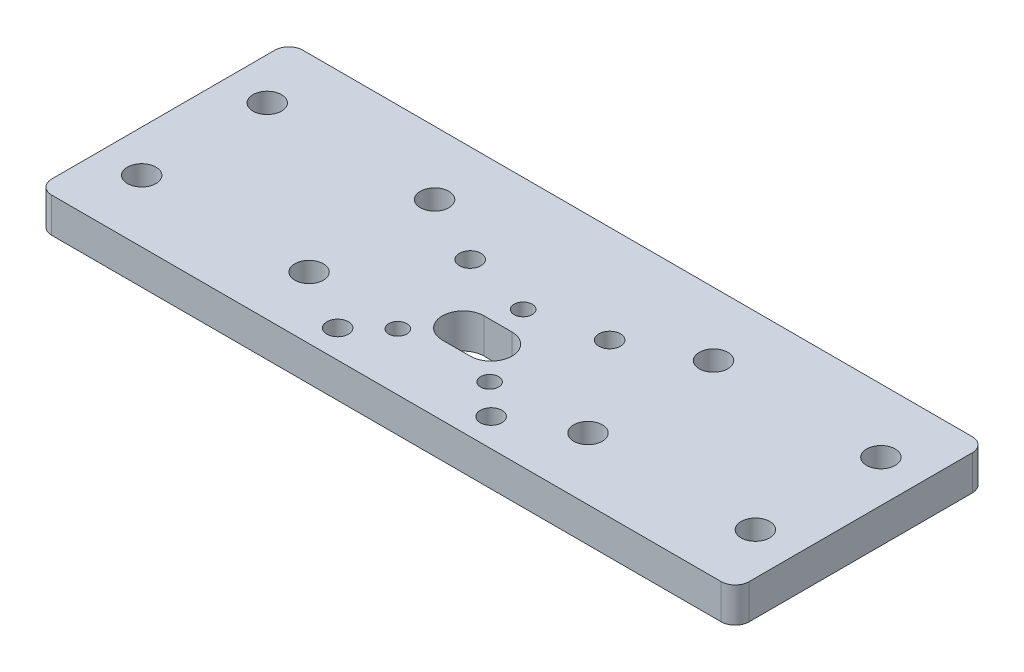
SolidWorks part; units mm, degrees
ref_plane "Front Plane" through (0, 0, 0) normal (0, 0, 1) x (1, 0, 0)
ref_plane "Top Plane" through (0, 0, 0) normal (0, 1, 0) x (1, 0, 0)
ref_plane "Right Plane" through (0, 0, 0) normal (1, 0, 0) x (0, 0, -1)
sketch "Sketch1" plane through (0, 0, 0) normal (0, 1, 0) x (1, 0, 0)
  line L0 (0, 0) -> (58.0583, 0) construction
  line L1 (0, 0) -> (0, -51.632) construction
  line L7 (-3.5, -8) -> (3.5, -8) construction
  line L8 (-48, -12) -> (48, -12)
  line L10 (2, 4) -> (-2, 4)
  line L11 (2, -2) -> (-2, -2)
  line L12 (-50, -10) -> (-50, 22)
  line L13 (-48, 24) -> (48, 24)
  line L14 (50, -10) -> (50, 22)
  line L15 (-50, -12) -> (50, 24) construction
  line L16 (-50, 24) -> (50, -12) construction
  circle A0 centre (0, 0) radius 7.6 construction
  circle A1 centre (0, 7.6) radius 1.3
  circle A2 centre (6.5818, -3.8) radius 1.3
  circle A3 centre (-6.5818, -3.8) radius 1.3
  arc A6 (2, -2) -> (2, 4) centre (2, 1) ccw
  arc A7 (-2, -2) -> (-2, 4) centre (-2, 1) cw
  circle A8 centre (44, 14.9) radius 2.05
  circle A9 centre (20, 14.9) radius 2.05
  circle A10 centre (44, -3.1) radius 2.05
  circle A11 centre (20, -3.1) radius 2.05
  circle A12 centre (-44, -3.1) radius 2.05
  circle A13 centre (-20, -3.1) radius 2.05
  circle A14 centre (-20, 14.9) radius 2.05
  circle A15 centre (-44, 14.9) radius 2.05
  arc A16 (48, 24) -> (50, 22) centre (48, 22) cw
  arc A17 (48, -12) -> (50, -10) centre (48, -10) ccw
  arc A18 (-48, -12) -> (-50, -10) centre (-48, -10) cw
  arc A19 (-50, 22) -> (-48, 24) centre (-48, 22) cw
  circle A20 centre (11, -8) radius 1.55
  circle A21 centre (10, 10) radius 1.55
  circle A22 centre (-11, -8) radius 1.55
  circle A23 centre (-10, 10) radius 1.55
  point P4 (0, 0)
  point P7 (0, 6)
  point P23 (0, 2.5)
  point P28 (0, -2.5)
  point P32 (0, 4)
  point P36 (0, -2)
  point P37 (0, -8)
  dimension "D3" = 15.2
  dimension "D4" = 2.6
  dimension "D5" = 120
  dimension "D6" = 4
  dimension "D7" = 3
  dimension "D9" = 3
  dimension "D11" = 24
  dimension "D12" = 18
  dimension "D13" = 4.1
  dimension "D14" = 8.9
  dimension "D15" = 20
  dimension "D16" = 8
  dimension "D10" = 8.2
  dimension "D18" = 2
  dimension "D19" = 3.1
  dimension "D20" = 11
  dimension "D21" = 8
  dimension "D22" = 10
  dimension "D23" = 10
  dimension "D1" = 100
  dimension "D2" = 36
  dimension "D8" = 1
  dimension "D17" = 7
extrude "Boss-Extrude1" add sketch "Sketch1" along normal blind 5
